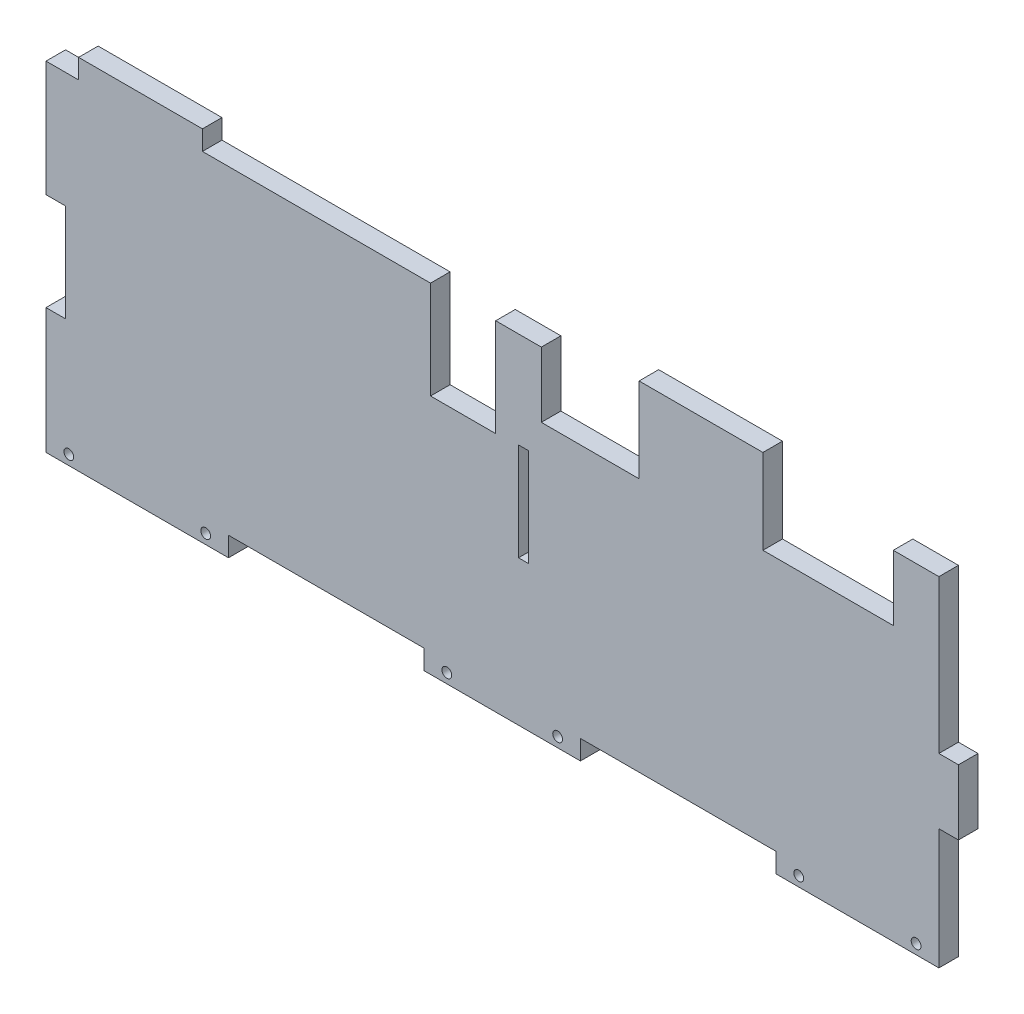
SolidWorks part; units mm, degrees
ref_plane "Plan de face" through (0, 0, 0) normal (0, 0, 1) x (1, 0, 0)
ref_plane "Plan de dessus" through (0, 0, 0) normal (0, 1, 0) x (1, 0, 0)
ref_plane "Plan de droite" through (0, 0, 0) normal (1, 0, 0) x (0, 0, -1)
sketch "Esquisse2" plane through (0, 0, 0) normal (0, 0, 1) x (1, 0, 0)
  line L1 (0, 0) -> (-330, 0)
  line L2 (0, 0) -> (0, 110)
  line L3 (0, 110) -> (-330, 110)
  line L4 (-330, 0) -> (-330, 110)
  dimension "D1" = 110
  dimension "D2" = 330
extrude "Boss.-Extru.1" add sketch "Esquisse2" along normal blind 6
sketch "Esquisse3" plane through (0, 0, 6) normal (0, 0, 1) x (1, 0, 0)
  line L0 (-330, 0) -> (0, 0) construction
  line L1 (-60, 110) -> (0, 110)
  line L2 (0, 110) -> (0, 57)
  line L3 (0, 57) -> (-6, 57)
  line L4 (-6, 104) -> (-6, 57)
  line L5 (0, 0) -> (-6, 0)
  line L6 (0, 0) -> (0, 37)
  line L7 (0, 37) -> (-6, 37)
  line L8 (-6, 0) -> (-6, 37)
  line L9 (-330, 110) -> (-270, 110)
  line L10 (0, 0) -> (0, 110) construction
  line L11 (-6, 104) -> (-20, 104)
  line L12 (-60, 110) -> (-60, 84)
  line L13 (-56, 0) -> (-116, 0)
  line L14 (-56, 0) -> (-56, 6)
  line L15 (-56, 6) -> (-116, 6)
  line L16 (-116, 0) -> (-116, 6)
  line L17 (0, 110) -> (-330, 110) construction
  line L18 (-164, 0) -> (-224, 0)
  line L19 (-164, 0) -> (-164, 6)
  line L20 (-164, 6) -> (-224, 6)
  line L21 (-224, 0) -> (-224, 6)
  line L22 (-280, 68.5) -> (-274, 68.5)
  line L23 (-280, 68.5) -> (-280, 38.5)
  line L24 (-280, 38.5) -> (-274, 38.5)
  line L25 (-274, 68.5) -> (-274, 38.5)
  line L26 (-20, 104) -> (-20, 84)
  line L27 (-330, 110) -> (-330, 59)
  line L28 (-330, 59) -> (-324, 59)
  line L29 (-324, 104) -> (-324, 59)
  line L30 (-330, 0) -> (-324, 0)
  line L31 (-330, 0) -> (-330, 39)
  line L32 (-330, 39) -> (-324, 39)
  line L33 (-324, 0) -> (-324, 39)
  line L34 (-98, 110) -> (-98, 84)
  line L35 (-128, 104) -> (-128, 84)
  line L36 (-324, 104) -> (-270, 104)
  line L37 (-270, 110) -> (-270, 104)
  line L38 (-232, 110) -> (-98, 110)
  line L39 (-128, 104) -> (-142, 104)
  line L40 (-232, 104) -> (-232, 110)
  line L41 (-20, 84) -> (-60, 84)
  line L42 (-128, 84) -> (-98, 84)
  line L43 (-135, 74.5) -> (-132, 74.5)
  line L44 (-135, 74.5) -> (-135, 44.5)
  line L45 (-135, 44.5) -> (-132, 44.5)
  line L46 (-132, 74.5) -> (-132, 44.5)
  line L47 (-142, 104) -> (-142, 74)
  line L48 (-142, 74) -> (-162, 74)
  line L49 (-162, 74) -> (-162, 104)
  line L50 (-162, 104) -> (-232, 104)
  dimension "D1" = 6
  dimension "D2" = 20
  dimension "D3" = 37
  dimension "D4" = 6
  dimension "D5" = 20
  dimension "D6" = 38
  dimension "D7" = 6
  dimension "D8" = 6
  dimension "D9" = 6
  dimension "D10" = 6
  dimension "D11" = 6
  dimension "D12" = 3
  dimension "D13" = 50
  dimension "D14" = 60
  dimension "D15" = 6
  dimension "D16" = 60
  dimension "D17" = 48
  dimension "D18" = 6
  dimension "D19" = 134
  dimension "D20" = 60
  dimension "D21" = 9.5
  dimension "D22" = 39
  dimension "D23" = 20
  dimension "D24" = 30
  dimension "D25" = 41.5
  dimension "D26" = 44
  dimension "D27" = 132
  dimension "D28" = 20
  dimension "D29" = 30
  dimension "D30" = 20
  dimension "D31" = 30
  dimension "D32" = 40
  dimension "D33" = 38
  dimension "D34" = 30
  dimension "D35" = 14
  dimension "D36" = 6
  dimension "D37" = 6
extrude "Enlèv. mat.-Extru.1" cut sketch "Esquisse3" against normal through all
sketch "Esquisse4" plane through (0, 0, 6) normal (0, 0, 1) x (1, 0, 0)
  line L0 (-324, 104) -> (-270, 104) construction
  line L1 (-280, 104) -> (-336.7992, 104)
  line L2 (-280, 104) -> (-280, 0)
  line L3 (-280, 0) -> (-336.7992, 0)
  line L4 (-336.7992, 104) -> (-336.7992, 0)
  line L5 (-280, 68.5) -> (-280, 38.5) construction
  line L6 (-324, 0) -> (-224, 0) construction
  dimension "D1" = 0
  dimension "D2" = 0
extrude "Enlèv. mat.-Extru.2" cut sketch "Esquisse4" against normal through all
sketch "Esquisse5" plane through (0, 0, 0) normal (0, 0, -1) x (-1, 0, 0)
  line L0 (280, 0) -> (280, 38.5) construction
  line L1 (280, 0) -> (224, 0) construction
  line L2 (224, 6) -> (224, 0) construction
  line L3 (116, 6) -> (116, 0) construction
  line L4 (164, 0) -> (116, 0) construction
  line L5 (164, 0) -> (164, 6) construction
  line L6 (56, 0) -> (56, 6) construction
  line L7 (56, 0) -> (6, 0) construction
  line L8 (6, 37) -> (6, 0) construction
  circle A0 centre (13, 3) radius 1.5
  circle A1 centre (49, 3) radius 1.5
  circle A2 centre (123, 3) radius 1.5
  circle A3 centre (157, 3) radius 1.5
  circle A4 centre (231, 3) radius 1.5
  circle A5 centre (273, 3) radius 1.5
  point P16 (224, 3)
  point P19 (116, 3)
  dimension "D1" = 3
  dimension "D2" = 7
  dimension "D3" = 3
  dimension "D4" = 3
  dimension "D5" = 7
  dimension "D6" = 3
  dimension "D7" = 3
  dimension "D8" = 7
  dimension "D9" = 3
  dimension "D10" = 3
  dimension "D12" = 3
  dimension "D13" = 3
  dimension "D14" = 7
  dimension "D15" = 3
  dimension "D16" = 3
  dimension "D17" = 7
  dimension "D18" = 3
  dimension "D11" = 7
extrude "Enlèv. mat.-Extru.3" cut sketch "Esquisse5" against normal through all
sketch "Esquisse6" plane through (0, 0, 0) normal (0, 0, -1) x (-1, 0, 0)
  circle A0 centre (13, 3) radius 2.995
  circle A1 centre (49, 3) radius 2.995
  circle A2 centre (123, 3) radius 2.995
  circle A3 centre (157, 3) radius 2.995
  circle A4 centre (273, 3) radius 2.995
  circle A5 centre (231, 3) radius 2.995
  dimension "D1" = 5.99
  dimension "D2" = 5.99
  dimension "D3" = 5.99
  dimension "D4" = 5.99
  dimension "D5" = 5.99
  dimension "D6" = 5.99
extrude "Enlèv. mat.-Extru.5" cut sketch "Esquisse6" against normal blind 3
